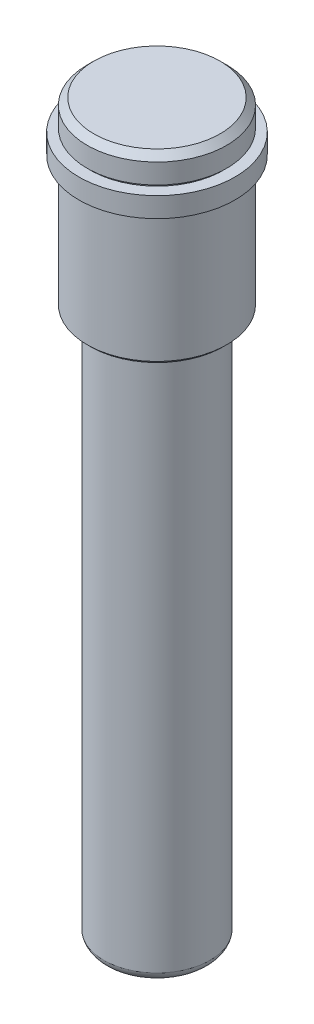
SolidWorks part; units mm, degrees
ref_plane "Płaszczyzna przednia" through (0, 0, 0) normal (0, 0, 1) x (1, 0, 0)
ref_plane "Płaszczyzna górna" through (0, 0, 0) normal (0, 1, 0) x (1, 0, 0)
ref_plane "Płaszczyzna prawa" through (0, 0, 0) normal (1, 0, 0) x (0, 0, -1)
sketch "Szkic1" plane through (0, 0, 0) normal (0, 0, 1) x (1, 0, 0)
  line L0 (0, 0) -> (0, 188.8022) construction
  line L1 (0, 188.8022) -> (-19, 188.8022)
  line L2 (-21, 186.8022) -> (-21, 180.8022)
  line L3 (-20, 179.8022) -> (-23.5, 179.8022)
  line L4 (-23.5, 179.8022) -> (-23.5, 173.8022)
  line L5 (-23.5, 173.8022) -> (-21, 173.8022)
  line L6 (-21, 173.1022) -> (-21, 134.8022)
  line L7 (-13.2788, -31.1978) -> (0, -31.1978)
  line L8 (-16, 132.8022) -> (-16, -28.1978)
  line L9 (-20, 133.8022) -> (-15, 133.8022)
  line L10 (-21, 180.8022) -> (-20, 180.8022)
  line L11 (-20, 180.8022) -> (-20, 179.8022)
  line L12 (-19, 188.8022) -> (-21, 186.8022)
  line L13 (-21, 173.8022) -> (-20.3, 173.8022)
  line L14 (-20.3, 173.8022) -> (-20.3, 173.1022)
  line L15 (-20.3, 173.1022) -> (-21, 173.1022)
  line L16 (0, 188.8022) -> (0, -31.1978)
  line L17 (-21, 134.8022) -> (-20, 133.8022)
  line L19 (-15, 133.8022) -> (-15, 132.8022)
  line L20 (-15, 132.8022) -> (-16, 132.8022)
  line L21 (-16, -28.1978) -> (-10.9261, -28.1978) construction
  arc A0 (-16, -28.1978) -> (-13.2788, -31.1978) centre (-12.0844, -27.3803) ccw
  point P4 (-21, 188.8022)
  point P10 (-21, 133.8022)
  dimension "D1" = 46
  dimension "D2" = 21
  dimension "D3" = 21
  dimension "D4" = 23.5
  dimension "D5" = 6
  dimension "D6" = 3
  dimension "D7" = 16
  dimension "D8" = 165
revolve "Obrót2" add sketch "Szkic1" angle 360 about L16
